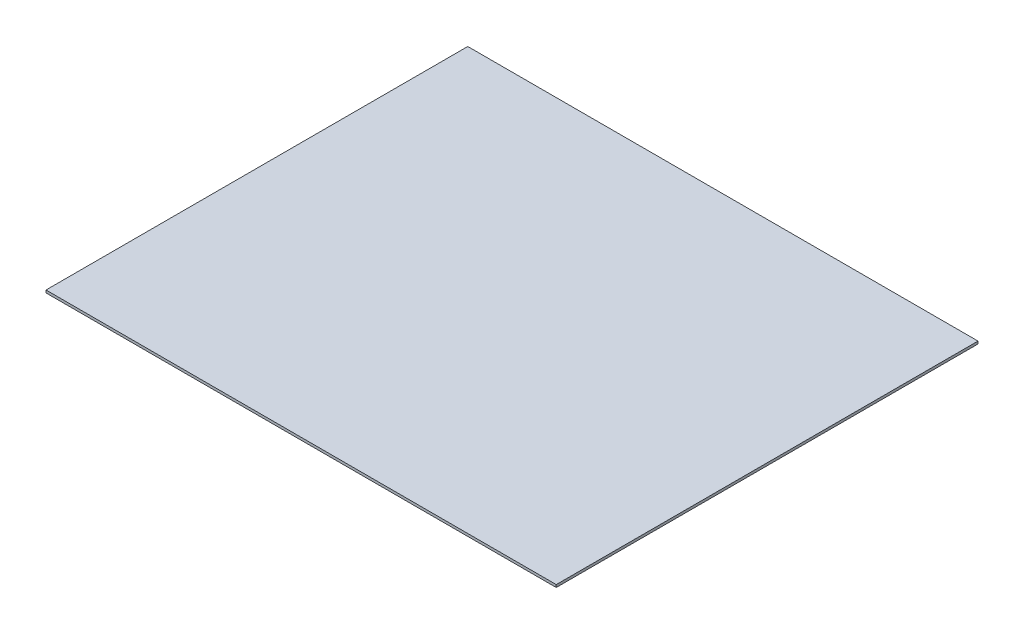
SolidWorks part; units mm, degrees
material "Polyetheretherketone (PEEK)"
ref_plane "X-Y Datum" through (0, 0, 0) normal (0, 0, 1) x (1, 0, 0)
ref_plane "X-Z Datum" through (0, 0, 0) normal (0, 1, 0) x (1, 0, 0)
ref_plane "Y-Z Datum" through (0, 0, 0) normal (1, 0, 0) x (0, 0, -1)
sketch "Sketch1" plane through (0, 0, 0) normal (0, 1, 0) x (1, 0, 0)
  line L0 (-278.4801, 264.4399) -> (356.1527, 264.4399)
  line L1 (-278.4801, 264.4399) -> (-278.4801, -260.1438)
  line L2 (-278.4801, -260.1438) -> (356.1527, -260.1438)
  line L3 (356.1527, 264.4399) -> (356.1527, -260.1438)
extrude "Boss-Extrude1" add sketch "Sketch1" along normal blind 3.175
